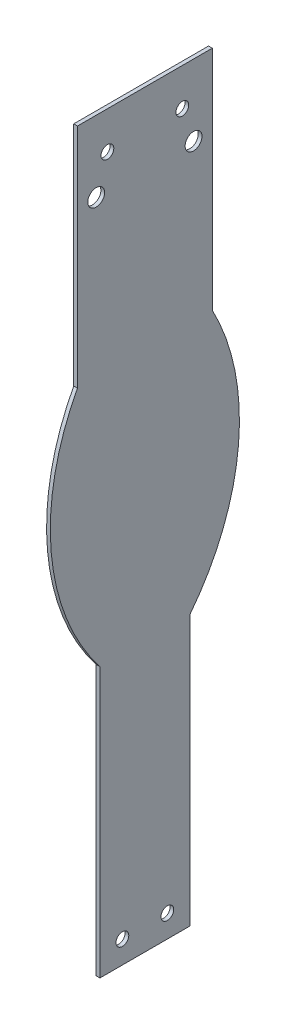
SolidWorks part; units mm, degrees
material "PVC 0.007 Plasticized"
ref_plane "Front Plane" through (0, 0, 0) normal (0, 0, 1) x (1, 0, 0)
ref_plane "Top Plane" through (0, 0, 0) normal (0, 1, 0) x (1, 0, 0)
ref_plane "Right Plane" through (0, 0, 0) normal (1, 0, 0) x (0, 0, -1)
sketch "Sketch1" plane through (0, 0, 0) normal (1, 0, 0) x (0, 0, -1)
  line L0 (12, -200) -> (12, -128)
  line L5 (-18, 0) -> (18, 0)
  line L6 (-18, 0) -> (-18, -200) construction
  line L7 (-18, -200) -> (18, -200) construction
  line L8 (18, 0) -> (18, -200) construction
  line L9 (-18, 0) -> (18, -200) construction
  line L10 (-18, -200) -> (18, 0) construction
  line L11 (-12, -200) -> (-12, -128)
  line L12 (12, -128) -> (-12, -128) construction
  line L13 (18, -60.6171) -> (-18, -60.6171) construction
  line L14 (18, 0) -> (18, -60.6171)
  line L15 (-18, 0) -> (-18, -60.6171)
  line L16 (12, -200) -> (-12, -200)
  arc A0 (18, -60.6171) -> (12, -128) centre (-36.7557, -89.7001) cw
  arc A1 (-18, -60.6171) -> (-12, -128) centre (36.7557, -89.7001) ccw
  point P4 (0, -100)
  point P5 (0, 0)
  point P18 (-25, -95.199)
  point P19 (0, -200)
  point P20 (0, -200)
  dimension "D2" = 62
  dimension "D3" = 62
  dimension "D1" = 200
  dimension "D4" = 24
  dimension "D5" = 36
  dimension "D6" = 72
  dimension "D7" = 25
extrude "Boss-Extrude1" add sketch "Sketch1" along normal blind 1 contours L5 L14 A0 L0 L16 L11 A1 L15
hole_wizard "M4 Clearance Hole1" positions "Sketch2" profile "Sketch3" hole size "M4" standard "ISO" end condition through all
sketch "Sketch2" plane through (0, 0, 0) normal (-1, 0, 0) x (0, 0, 1)
  point P0 (13, -19)
  point P3 (-13, -19)
sketch "Sketch3" plane through (0, -19, 13) normal (0, 1, 0) x (0, 0, 1)
  line L0 (0, 0) -> (0, 1)
  line L1 (0, 1) -> (2.25, 1)
  line L2 (2.25, 1) -> (2.25, 0)
  line L5 (2.25, 0) -> (0, 0)
  line L11 (0, -6.35) -> (0, 107.95) construction
  dimension "Thru Hole Dia." = 4.5
  dimension "Thru Hole Depth" = 1
hole_wizard "M3 Clearance Hole1" positions "Sketch4" profile "Sketch5" hole size "M3" standard "ISO" end condition through all
sketch "Sketch4" plane through (0, 0, 0) normal (-1, 0, 0) x (0, 0, 1)
  point P0 (-10, -10)
  point P3 (10, -10)
sketch "Sketch5" plane through (0, -10, -10) normal (0, 1, 0) x (0, 0, 1)
  line L0 (0, 0) -> (0, 1)
  line L1 (0, 1) -> (1.7, 1)
  line L2 (1.7, 1) -> (1.7, 0)
  line L5 (1.7, 0) -> (0, 0)
  line L11 (0, -6.35) -> (0, 107.95) construction
  dimension "Thru Hole Dia." = 3.4
  dimension "Thru Hole Depth" = 1
hole_wizard "M3 Clearance Hole2" positions "Sketch6" profile "Sketch7" hole size "M3" standard "ISO" end condition through all
sketch "Sketch6" plane through (0, 0, 0) normal (-1, 0, 0) x (0, 0, 1)
  line L0 (-12, -200) -> (12, -200) construction
  point P0 (6, -194)
  point P2 (-6, -194)
  dimension "D1" = 12
  dimension "D2" = 6
  dimension "D3" = 6
sketch "Sketch7" plane through (0, -194, 6) normal (0, 1, 0) x (0, 0, 1)
  line L0 (0, 0) -> (0, 1)
  line L1 (0, 1) -> (1.7, 1)
  line L2 (1.7, 1) -> (1.7, 0)
  line L5 (1.7, 0) -> (0, 0)
  line L11 (0, -6.35) -> (0, 107.95) construction
  dimension "Thru Hole Dia." = 3.4
  dimension "Thru Hole Depth" = 1
